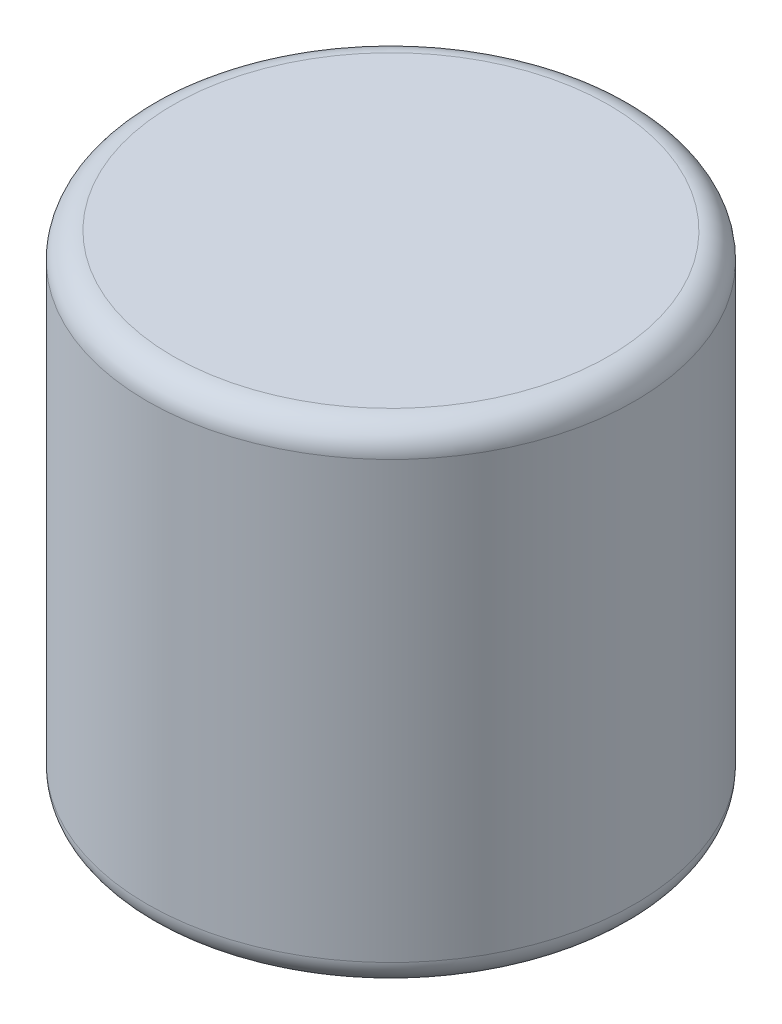
SolidWorks part; units mm, degrees
material "Gray Cast Iron"
ref_plane "Front Plane" through (0, 0, 0) normal (0, 0, 1) x (1, 0, 0)
ref_plane "Top Plane" through (0, 0, 0) normal (0, 1, 0) x (1, 0, 0)
ref_plane "Right Plane" through (0, 0, 0) normal (1, 0, 0) x (0, 0, -1)
sketch "Sketch1" plane through (0, 0, 0) normal (0, 1, 0) x (1, 0, 0)
  circle A0 centre (0, 0) radius 2.3876
  dimension "OD" = 4.7752
extrude "Boss-Extrude1" add sketch "Sketch1" along normal mid plane 4.7752
fillet "Fillet1" radius 0.254 2 edges at (0, -2.3876, 2.3876) (0, 2.3876, 2.3876)
